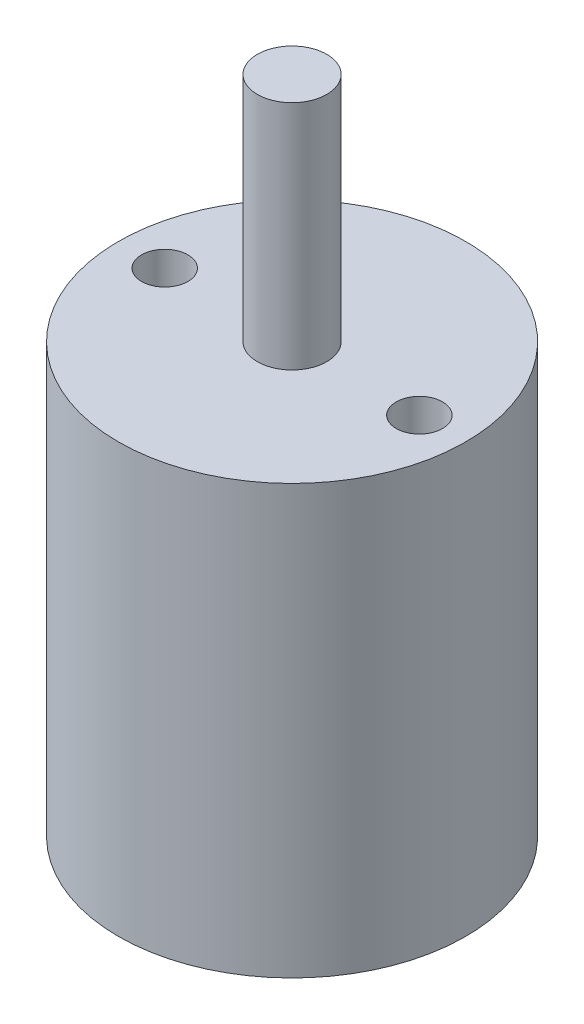
SolidWorks part; units mm, degrees
ref_plane "前视基准面" through (0, 0, 0) normal (0, 0, 1) x (1, 0, 0)
ref_plane "上视基准面" through (0, 0, 0) normal (0, 1, 0) x (1, 0, 0)
ref_plane "右视基准面" through (0, 0, 0) normal (1, 0, 0) x (0, 0, -1)
sketch "草图1" plane through (0, 0, 0) normal (0, 1, 0) x (1, 0, 0)
  circle A0 centre (0, 0) radius 7.5
  dimension "D1" = 15
extrude "凸台-拉伸1" add sketch "草图1" along normal blind 18.5
sketch "草图2" plane through (0, 18.5, 0) normal (0, 1, 0) x (1, 0, 0)
  circle A0 centre (0, 0) radius 1.5
  dimension "D1" = 3
extrude "凸台-拉伸2" add sketch "草图2" along normal blind 10
sketch "草图3" plane through (0, 18.5, 0) normal (0, 1, 0) x (1, 0, 0)
  line L0 (-5.5, 0) -> (5.5, 0) construction
  circle A0 centre (-5.5, 0) radius 1
  circle A1 centre (5.5, 0) radius 1
  point P4 (0, 0)
  dimension "D2" = 2
  dimension "D3" = 2
  dimension "D1" = 11
extrude "切除-拉伸1" cut sketch "草图3" against normal blind 10
